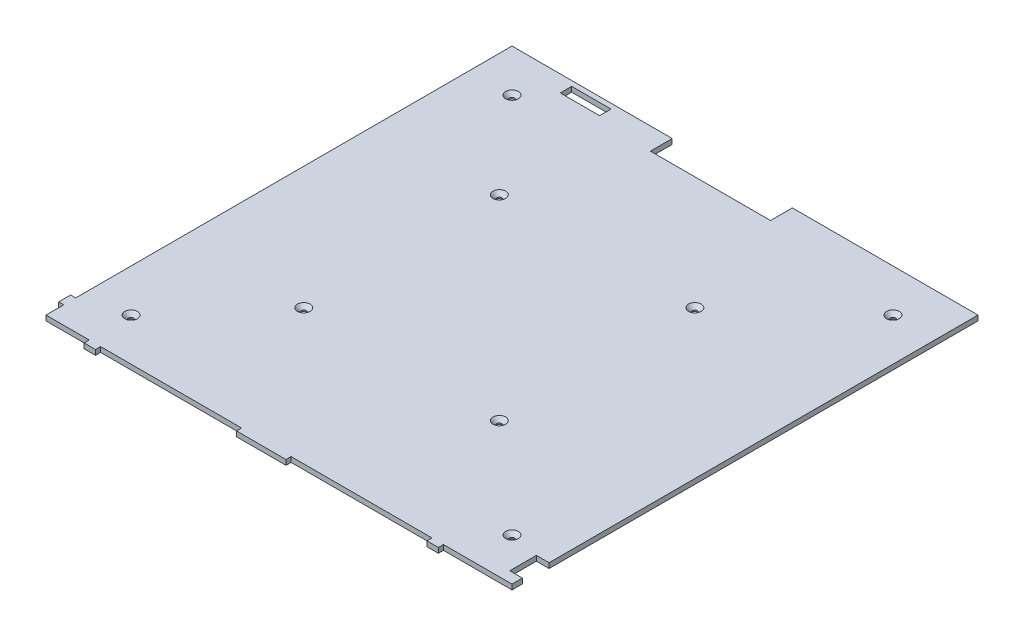
SolidWorks part; units mm, degrees
ref_plane "Front Plane" through (0, 0, 0) normal (0, 0, 1) x (1, 0, 0)
ref_plane "Top Plane" through (0, 0, 0) normal (0, 1, 0) x (1, 0, 0)
ref_plane "Right Plane" through (0, 0, 0) normal (1, 0, 0) x (0, 0, -1)
sketch "Sketch1" plane through (0, 0, 0) normal (0, 1, 0) x (1, 0, 0)
  line L0 (-75, -94) -> (-70, -94) construction
  line L1 (-75, -92) -> (-75, -94) construction
  line L2 (-92, -92) -> (-75, -92) construction
  line L3 (-92, -85) -> (-92, -92) construction
  line L4 (-94, -85) -> (-92, -85) construction
  line L5 (-94, -79.8) -> (-94, -85) construction
  line L6 (-92, -79.8) -> (-94, -79.8) construction
  line L7 (-92, 92) -> (-92, -79.8) construction
  line L8 (-28.4, 92) -> (-92, 92) construction
  line L9 (-28.4, 83.4) -> (-28.4, 92) construction
  line L10 (18.4, 83.4) -> (-28.4, 83.4) construction
  line L11 (18.4, 92) -> (18.4, 83.4) construction
  line L12 (92, 92) -> (18.4, 92) construction
  line L13 (92, -77.4) -> (92, 92) construction
  line L14 (87, -77.4) -> (92, -77.4) construction
  line L15 (87, -87.4) -> (87, -77.4) construction
  line L16 (92, -87.4) -> (87, -87.4) construction
  line L17 (92, -92) -> (92, -87.4) construction
  line L18 (65, -92) -> (92, -92) construction
  line L19 (65, -94) -> (65, -92) construction
  line L20 (60, -94) -> (65, -94) construction
  line L21 (60, -92) -> (60, -94) construction
  line L22 (5, -92) -> (60, -92) construction
  line L23 (5, -94) -> (5, -92) construction
  line L24 (-15, -94) -> (5, -94) construction
  line L25 (-15, -92) -> (-15, -94) construction
  line L26 (-70, -92) -> (-15, -92) construction
  line L27 (-70, -94) -> (-70, -92) construction
  line L28 (-74.75, -93.75) -> (-70.25, -93.75)
  line L29 (-70.25, -93.75) -> (-70.25, -91.75)
  line L30 (-70.25, -91.75) -> (-14.75, -91.75)
  line L31 (-14.75, -91.75) -> (-14.75, -93.75)
  line L32 (-14.75, -93.75) -> (4.75, -93.75)
  line L33 (4.75, -93.75) -> (4.75, -91.75)
  line L34 (4.75, -91.75) -> (60.25, -91.75)
  line L35 (60.25, -91.75) -> (60.25, -93.75)
  line L36 (60.25, -93.75) -> (64.75, -93.75)
  line L37 (64.75, -93.75) -> (64.75, -91.75)
  line L38 (64.75, -91.75) -> (91.75, -91.75)
  line L39 (91.75, -91.75) -> (91.75, -87.65)
  line L40 (91.75, -87.65) -> (86.75, -87.65)
  line L41 (86.75, -87.65) -> (86.75, -77.15)
  line L42 (86.75, -77.15) -> (91.75, -77.15)
  line L43 (91.75, -77.15) -> (91.75, 91.75)
  line L44 (91.75, 91.75) -> (18.65, 91.75)
  line L45 (18.65, 91.75) -> (18.65, 83.15)
  line L46 (18.65, 83.15) -> (-28.65, 83.15)
  line L47 (-28.65, 83.15) -> (-28.65, 91.75)
  line L48 (-28.65, 91.75) -> (-91.75, 91.75)
  line L49 (-91.75, 91.75) -> (-91.75, -80.05)
  line L50 (-91.75, -80.05) -> (-93.75, -80.05)
  line L51 (-93.75, -80.05) -> (-93.75, -84.75)
  line L52 (-93.75, -84.75) -> (-91.75, -84.75)
  line L53 (-91.75, -84.75) -> (-91.75, -91.75)
  line L54 (-91.75, -91.75) -> (-74.75, -91.75)
  line L55 (-74.75, -91.75) -> (-74.75, -93.75)
  dimension "D1" = 184
  dimension "D2" = 184
  dimension "D3" = 73.6
  dimension "D4" = 46.8
  dimension "D5" = 8.6
  dimension "D6" = 4.6
  dimension "D7" = 10
  dimension "D8" = 27
  dimension "D9" = 5
  dimension "D10" = 55
  dimension "D11" = 20
  dimension "D12" = 55
  dimension "D13" = 5
  dimension "D14" = 2
  dimension "D15" = 5.2
  dimension "D16" = 7
  dimension "D17" = 2
  dimension "D18" = 5
  dimension "D19" = 92
  dimension "D20" = 92
  dimension "D21" = 0.25
extrude "Boss-Extrude1" add sketch "Sketch1" along normal blind 2
sketch "Sketch2" plane through (0, 0, 0) normal (0, -1, 0) x (1, 0, 0)
  circle A0 centre (75, -75) radius 1
  circle A1 centre (-75, -75) radius 1
  circle A2 centre (-75, 75) radius 1
  circle A3 centre (75, 75) radius 1
  circle A4 centre (33.5, 38.5) radius 1
  circle A5 centre (-43.5, 38.5) radius 1
  circle A6 centre (-43.5, -38.5) radius 1
  circle A7 centre (33.5, -38.5) radius 1
  dimension "D1" = 2
  dimension "D2" = 2
  dimension "D3" = 2
  dimension "D4" = 2
  dimension "D5" = 2
  dimension "D6" = 2
  dimension "D7" = 2
  dimension "D8" = 2
extrude "Cut-Extrude1" cut sketch "Sketch2" against normal through all
chamfer "Chamfer1" distance 1.5 angle 45 8 edges at (75, 2, 74) (-75, 2, 74) (-43.5, 2, 37.5) (33.5, 2, 37.5) (33.5, 2, -39.5) (-43.5, 2, -39.5) (75, 2, -76) (-75, 2, -76)
sketch "Sketch3" plane through (0, 0, 0) normal (0, -1, 0) x (1, 0, 0)
  line L0 (-28.65, -91.75) -> (-91.75, -91.75) construction
  line L1 (-50.75, -89.75) -> (-66.25, -89.75)
  line L2 (-50.75, -89.75) -> (-50.75, -85.25)
  line L3 (-50.75, -85.25) -> (-66.25, -85.25)
  line L4 (-66.25, -89.75) -> (-66.25, -85.25)
  line L5 (-91.75, -91.75) -> (-91.75, 80.05) construction
  dimension "D1" = 2
  dimension "D2" = 25.5
  dimension "D3" = 15.5
  dimension "D4" = 4.5
extrude "Cut-Extrude2" cut sketch "Sketch3" against normal through all
sketch "Sketch4" plane through (0, 0, 0) normal (0, -1, 0) x (1, 0, 0)
  line L0 (-91.75, -91.75) -> (-91.75, 80.05) construction
  line L1 (-47.75, -20.25) -> (-39.75, -20.25)
  line L2 (-47.75, -20.25) -> (-47.75, 19.75)
  line L3 (-47.75, 19.75) -> (-39.75, 19.75)
  line L4 (-39.75, -20.25) -> (-39.75, 19.75)
  line L5 (-70.25, 91.75) -> (-14.75, 91.75) construction
  dimension "D1" = 44
  dimension "D2" = 8
  dimension "D3" = 40
  dimension "D4" = 72
extrude "Cut-Extrude3" cut sketch "Sketch4" against normal blind 1.3
